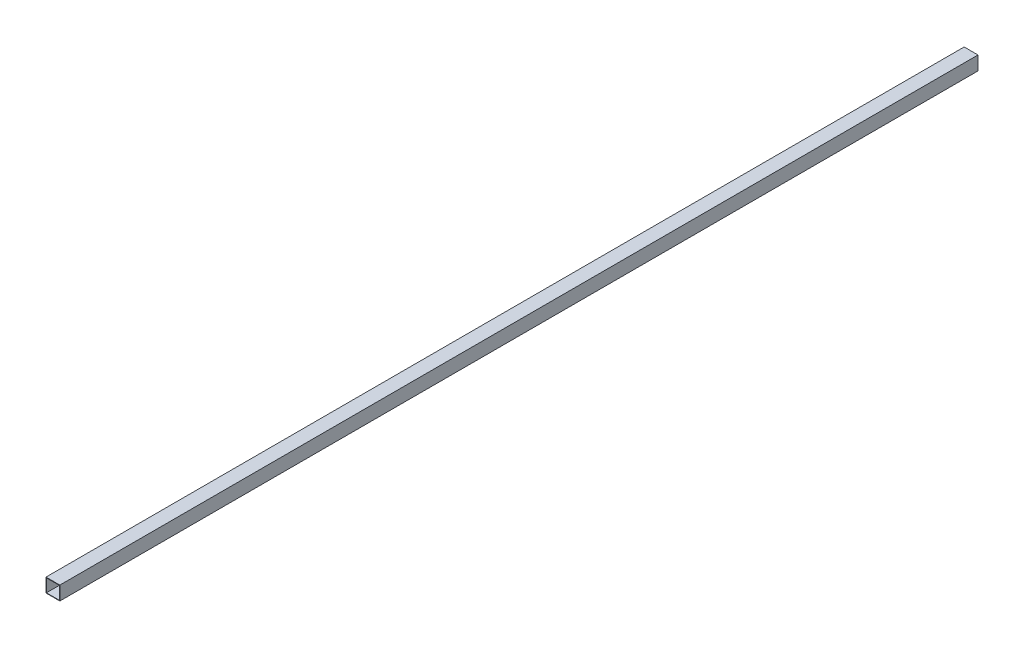
SolidWorks part; units mm, degrees
ref_plane "Alzado" through (0, 0, 0) normal (0, 0, 1) x (1, 0, 0)
ref_plane "Planta" through (0, 0, 0) normal (0, 1, 0) x (1, 0, 0)
ref_plane "Vista lateral" through (0, 0, 0) normal (1, 0, 0) x (0, 0, -1)
sketch "Croquis1" plane through (0, 0, 0) normal (0, 0, 1) x (1, 0, 0)
  line L1 (15, -15) -> (-15, -15)
  line L2 (15, -15) -> (15, 15)
  line L3 (15, 15) -> (-15, 15)
  line L4 (-15, -15) -> (-15, 15)
  line L5 (15, -15) -> (-15, 15) construction
  line L6 (15, 15) -> (-15, -15) construction
  circle A0 centre (0, 0) radius 21.2132 construction
  point P0 (0, 0)
  dimension "D1" = 30
extrude "Extruir-Lámina1" add sketch "Croquis1" along normal mid plane 1990 thin
